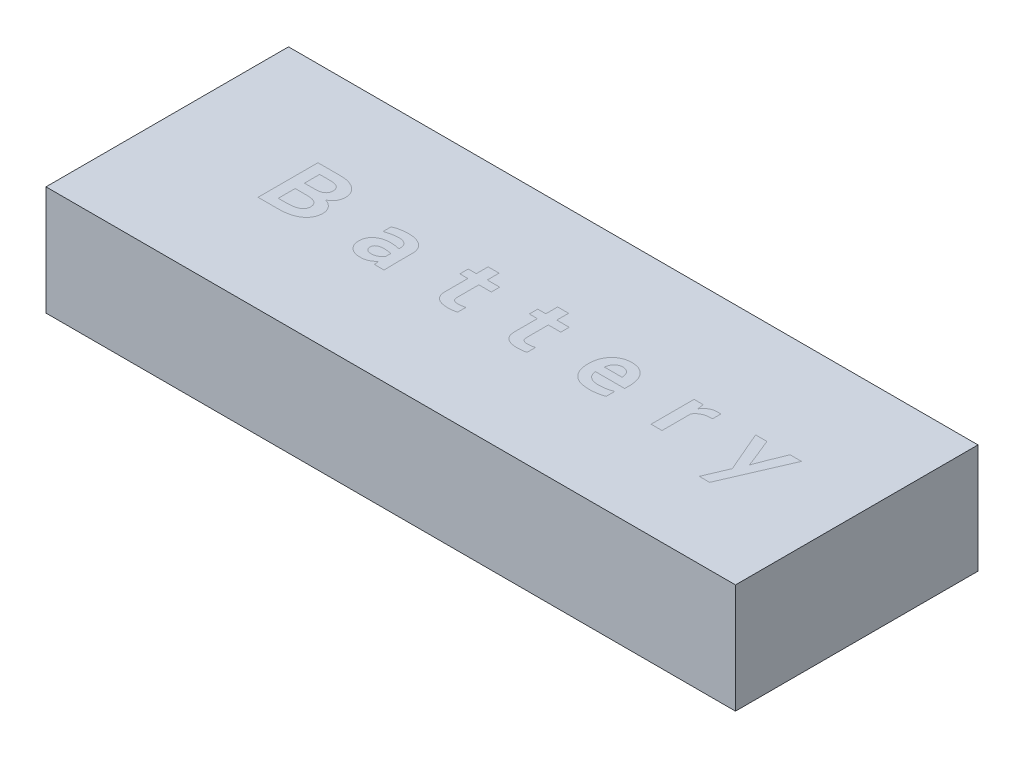
SolidWorks part; units mm, degrees
ref_plane "Front Plane" through (0, 0, 0) normal (0, 0, 1) x (1, 0, 0)
ref_plane "Top Plane" through (0, 0, 0) normal (0, 1, 0) x (1, 0, 0)
ref_plane "Right Plane" through (0, 0, 0) normal (1, 0, 0) x (0, 0, -1)
sketch "Sketch1" plane through (0, 0, 0) normal (0, 1, 0) x (1, 0, 0)
  line L1 (0, 0) -> (145, 0)
  line L2 (0, 0) -> (0, 51)
  line L3 (0, 51) -> (145, 51)
  line L4 (145, 0) -> (145, 51)
  dimension "D1" = 145
  dimension "D2" = 51
extrude "Boss-Extrude1" add sketch "Sketch1" along normal blind 23
sketch "Sketch2" plane through (0, 23, 0) normal (0, 1, 0) x (1, 0, 0)
  text T0 "Battery" font "Corbel" height in points 48
split line "Split Line1"
equation "\"leftedgewidth\" = 8.5mm"
equation "\"rightedgewidth\" = 10.75mm"
equation "\"innerclipwidth\" = 11.5mm"
equation "\"innerframewidth\" = 99.18mm"
equation "\"framelength\" = 103.2mm"
equation "\"frameextralength\" = 39mm"
equation "\"clipwidth\" = 3mm"
equation "\"cliplength\" = 6mm"
equation "\"clipheight\" = 8mm"
equation "\"basethickness\" = 5mm"
equation "\"framethickness\" = 1.6mm"
equation "\"batterylength\" = 145mm"
equation "\"batterywidth\" = 51mm"
equation "\"D1@Sketch1\"=\"batterylength\""
equation "\"D2@Sketch1\"=\"batterywidth\""
